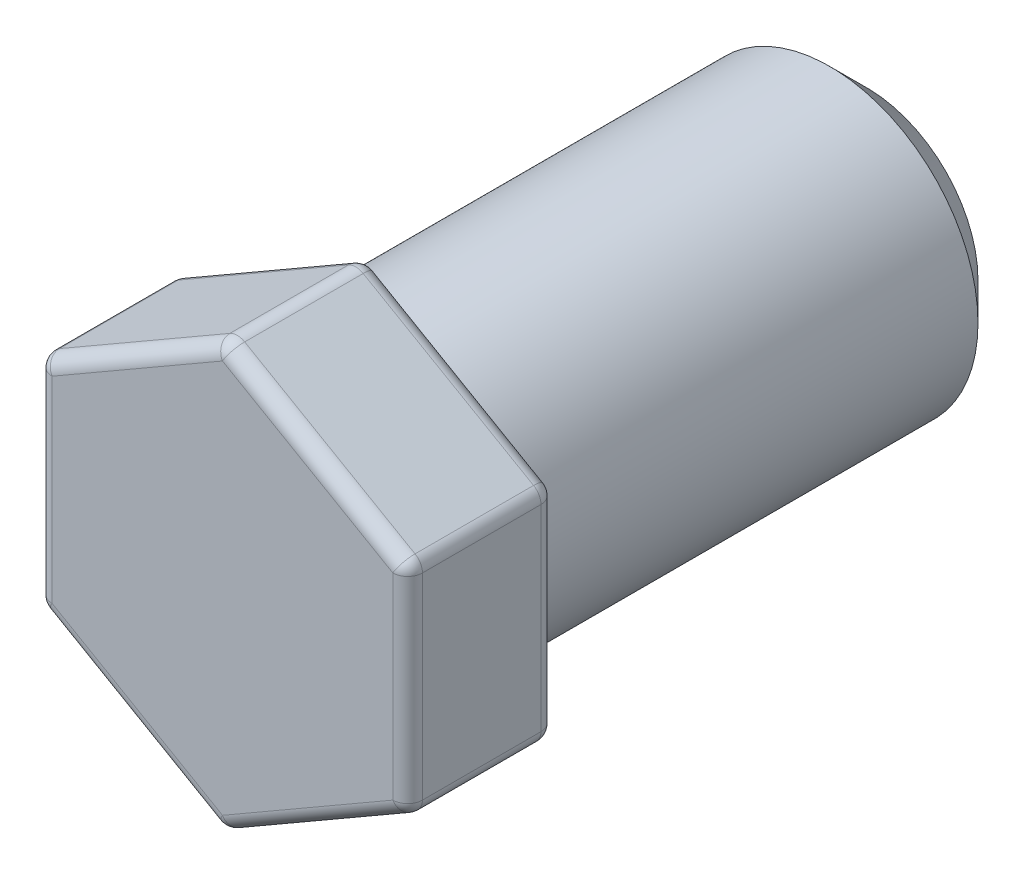
SolidWorks part; units mm, degrees
ref_plane "Front Plane" through (0, 0, 0) normal (0, 0, 1) x (1, 0, 0)
ref_plane "Top Plane" through (0, 0, 0) normal (0, 1, 0) x (1, 0, 0)
ref_plane "Right Plane" through (0, 0, 0) normal (1, 0, 0) x (0, 0, -1)
sketch "Sketch1" plane through (0, 0, 0) normal (0, 0, 1) x (1, 0, 0)
  circle A0 centre (0, 0) radius 2
  dimension "D1" = 4
extrude "Boss-Extrude1" add sketch "Sketch1" along normal blind 6.7
sketch "Sketch2" plane through (0, 0, 6.7) normal (0, 0, 1) x (1, 0, 0)
  line L1 (2.5, -1.4434) -> (2.5, 1.4434)
  line L2 (2.5, 1.4434) -> (0, 2.8868)
  line L3 (0, 2.8868) -> (-2.5, 1.4434)
  line L4 (-2.5, 1.4434) -> (-2.5, -1.4434)
  line L5 (-2.5, -1.4434) -> (0, -2.8868)
  line L6 (0, -2.8868) -> (2.5, -1.4434)
  circle A0 centre (0, 0) radius 2.5 construction
  dimension "D1" = 5
extrude "Boss-Extrude2" add sketch "Sketch2" along normal blind 2
fillet "Fillet1" radius 0.2 13 edges at (-1.25, -2.1651, 8.7) (-2.5, 0, 8.7) (-1.25, 2.1651, 8.7) (1.25, 2.1651, 8.7) (2.5, 0, 8.7) (1.25, -2.1651, 8.7) (2.5, 0, 6.7) (1.25, 2.1651, 6.7) (-1.25, 2.1651, 6.7) (-2.5, 0, 6.7) (-1.25, -2.1651, 6.7) (1.25, -2.1651, 6.7) (2, 0, 6.7)
fillet "Fillet2" radius 0.2 18 edges at (0, -2.8191, 8.6414) (0, -2.8191, 6.7586) (-2.4414, -1.4096, 8.6414) (-2.4414, -1.4096, 6.7586) (-2.4414, 1.4096, 8.6414) (-2.4414, 1.4096, 6.7586) (2.4414, 1.4096, 8.6414) (2.4414, 1.4096, 6.7586) (2.4414, -1.4096, 8.6414) (2.4414, -1.4096, 6.7586) (0, 2.8191, 8.6414) (0, 2.8191, 6.7586) (0, -2.8868, 7.7) (-2.5, -1.4434, 7.7) (-2.5, 1.4434, 7.7) (2.5, 1.4434, 7.7) (2.5, -1.4434, 7.7) (0, 2.8868, 7.7)
chamfer "Chamfer1" distance 0.5 angle 45 1 edges at (2, 0, 0)
